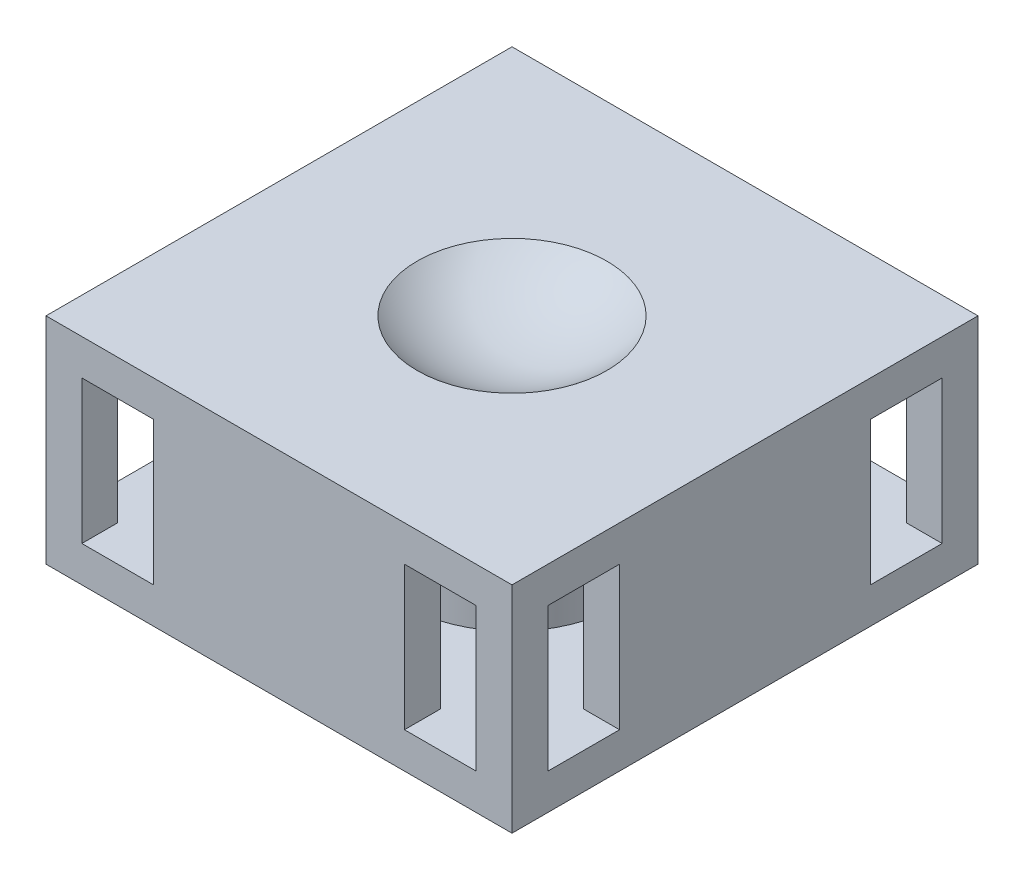
SolidWorks part; units mm, degrees
ref_plane "Front Plane" through (0, 0, 0) normal (0, 0, 1) x (1, 0, 0)
ref_plane "Top Plane" through (0, 0, 0) normal (0, 1, 0) x (1, 0, 0)
ref_plane "Right Plane" through (0, 0, 0) normal (1, 0, 0) x (0, 0, -1)
sketch "Sketch4" plane through (0, 0, 0) normal (0, 1, 0) x (1, 0, 0)
  line L1 (12.4409, 19.0972) -> (77.4409, 19.0972)
  line L2 (12.4409, 19.0972) -> (12.4409, -45.9028)
  line L3 (12.4409, -45.9028) -> (77.4409, -45.9028)
  line L4 (77.4409, 19.0972) -> (77.4409, -45.9028)
  dimension "D1" = 65
  dimension "D2" = 65
extrude "Boss-Extrude2" add sketch "Sketch4" against normal blind 45
sketch "Sketch5" plane through (0, 0, 0) normal (0, 1, 0) x (1, 0, 0)
  line L0 (24.9409, -13.4028) -> (64.9409, -13.4028)
  arc A0 (64.9409, -13.4028) -> (24.9409, -13.4028) centre (44.9409, -13.4028) ccw
  dimension "D1" = 40
revolve "Cut-Revolve2" cut sketch "Sketch5" angle 360 about L0
sketch "Sketch6" plane through (0, 0, 0) normal (0, 1, 0) x (1, 0, 0)
  line L1 (12.4409, 19.0972) -> (77.4409, 19.0972)
  line L2 (12.4409, 19.0972) -> (12.4409, -45.9028)
  line L3 (12.4409, -45.9028) -> (77.4409, -45.9028)
  line L4 (77.4409, 19.0972) -> (77.4409, -45.9028)
extrude "Cut-Extrude2" cut sketch "Sketch6" against normal blind 15
sketch "Sketch7" plane through (12.4409, 0, 0) normal (-1, 0, 0) x (0, 0, 1)
  line L0 (-19.0972, -45) -> (45.9028, -45) construction
  line L1 (-14.0972, -20) -> (-4.0972, -20)
  line L2 (-14.0972, -20) -> (-14.0972, -40)
  line L3 (-14.0972, -40) -> (-4.0972, -40)
  line L4 (-4.0972, -20) -> (-4.0972, -40)
  line L5 (-19.0972, -45) -> (-19.0972, -15) construction
  line L6 (30.9028, -40) -> (40.9028, -40)
  line L7 (30.9028, -20) -> (30.9028, -40)
  line L8 (30.9028, -20) -> (40.9028, -20)
  line L9 (40.9028, -20) -> (40.9028, -40)
  line L10 (45.9028, -45) -> (45.9028, -15) construction
  dimension "D1" = 20
  dimension "D2" = 5
  dimension "D3" = 5
  dimension "D4" = 10
  dimension "D5" = 5
extrude "Cut-Extrude3" cut sketch "Sketch7" against normal through all
sketch "Sketch8" plane through (0, 0, -19.0972) normal (0, 0, -1) x (-1, 0, 0)
  line L0 (-77.4409, -15) -> (-12.4409, -15) construction
  line L1 (-72.4409, -20) -> (-62.4409, -20)
  line L2 (-72.4409, -20) -> (-72.4409, -40)
  line L3 (-72.4409, -40) -> (-62.4409, -40)
  line L4 (-62.4409, -20) -> (-62.4409, -40)
  line L5 (-77.4409, -45) -> (-77.4409, -15) construction
  line L6 (-27.4409, -20) -> (-17.4409, -20)
  line L7 (-17.4409, -20) -> (-17.4409, -40)
  line L8 (-27.4409, -20) -> (-27.4409, -40)
  line L9 (-27.4409, -40) -> (-17.4409, -40)
  line L10 (-12.4409, -45) -> (-12.4409, -15) construction
  line L11 (-77.4409, -45) -> (-12.4409, -45) construction
  dimension "D1" = 10
  dimension "D2" = 5
  dimension "D3" = 5
  dimension "D4" = 20
  dimension "D5" = 5
  dimension "D6" = 5
extrude "Cut-Extrude4" cut sketch "Sketch8" against normal through all
fillet "Fillet1" radius 15 4 edges at (27.4409, -30, -4.0972) (27.4409, -30, 30.9028) (62.4409, -30, 30.9028) (62.4409, -30, -4.0972)
